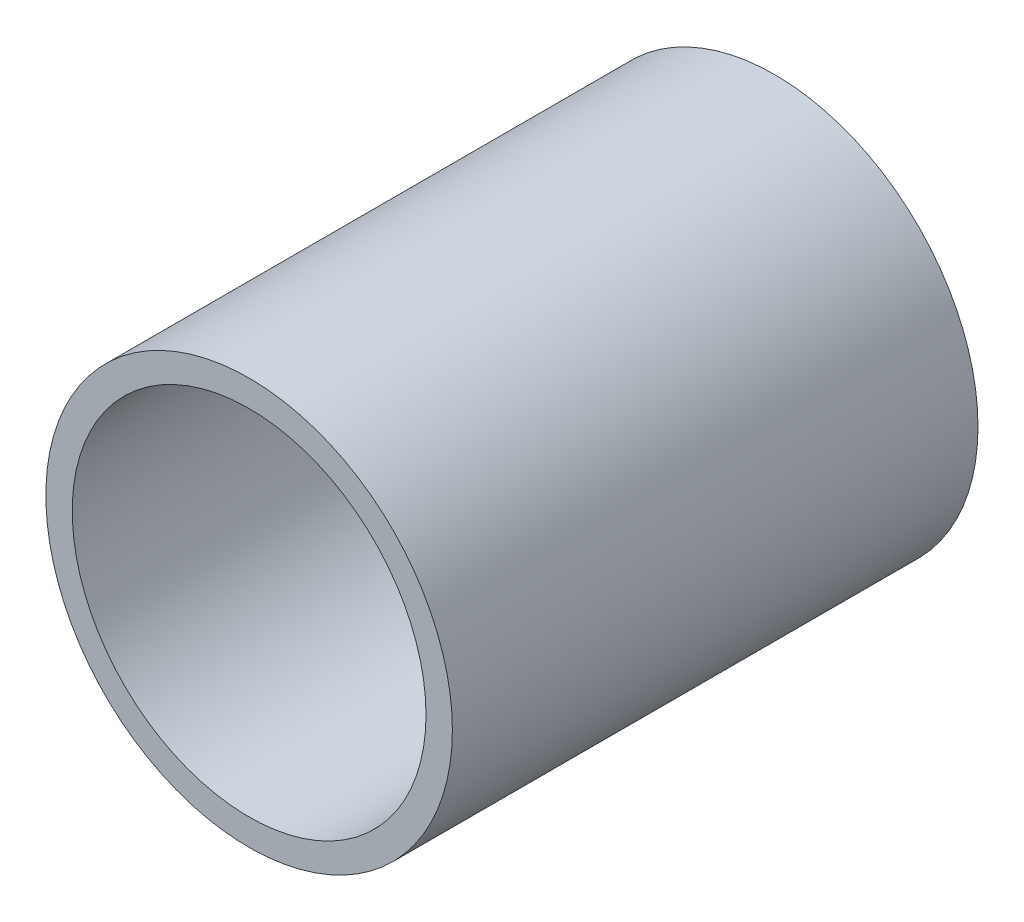
SolidWorks part; units mm, degrees
ref_plane "Front Plane" through (0, 0, 0) normal (0, 0, 1) x (1, 0, 0)
ref_plane "Top Plane" through (0, 0, 0) normal (0, 1, 0) x (1, 0, 0)
ref_plane "Right Plane" through (0, 0, 0) normal (1, 0, 0) x (0, 0, -1)
sketch "Sketch1" plane through (0, 0, 0) normal (0, 0, 1) x (1, 0, 0)
  circle A0 centre (0, 0) radius 30.1625
  dimension "Pipe OD" = 60.325
extrude "Extrude-Thin1" add sketch "Sketch1" along normal mid plane 78 thin thin type one direction reverse wall 3.9116
